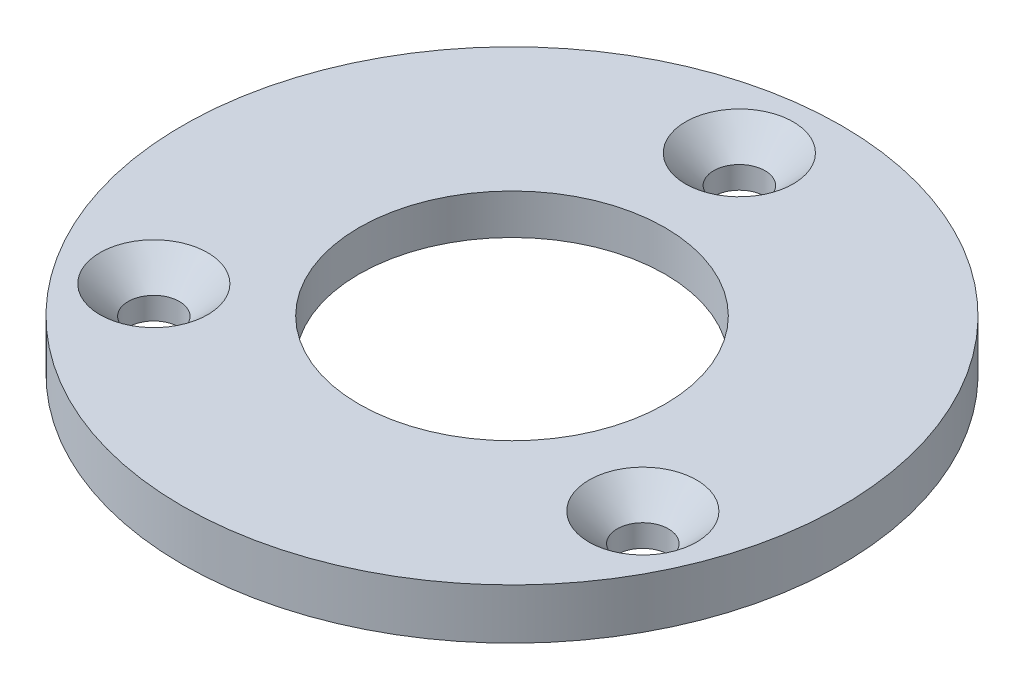
SolidWorks part; units mm, degrees
ref_plane "Front Plane" through (0, 0, 0) normal (0, 0, 1) x (1, 0, 0)
ref_plane "Top Plane" through (0, 0, 0) normal (0, 1, 0) x (1, 0, 0)
ref_plane "Right Plane" through (0, 0, 0) normal (1, 0, 0) x (0, 0, -1)
sketch "Sketch1" plane through (0, 0, 0) normal (0, 0, 1) x (1, 0, 0)
  line L0 (0, 0) -> (0, 10.3527) construction
  line L1 (-9.5504, 0) -> (-20.574, 0)
  line L2 (-20.574, 0) -> (-20.574, -3.1496)
  line L3 (-20.574, -3.1496) -> (-13.208, -3.1496)
  line L4 (-13.208, -3.1496) -> (-13.208, -2.5146)
  line L5 (-13.208, -2.5146) -> (-9.5504, -2.5146)
  line L6 (-9.5504, -2.5146) -> (-9.5504, 0)
  dimension "D1" = 20.574
  dimension "D2" = 9.5504
  dimension "D3" = 13.208
  dimension "D4" = 3.1496
  dimension "D5" = 0.635
revolve "Revolve1" add sketch "Sketch1" angle 360 about L0
hole_wizard "CSK for M3 SFHCS1" positions "Sketch3" profile "Sketch2" countersink size "M3" standard "ANSI Metric" end condition through all
sketch "Sketch3" plane through (0, 0, 0) normal (0, 1, 0) x (1, 0, 0)
  circle A0 centre (0, 0) radius 16.002 construction
  point P6 (-1.7156, 15.9098)
  point P15 (14.6361, -6.4691)
  point P16 (-12.9205, -9.4406)
  point P17 (0, 0)
  dimension "D1" = 32.004
  dimension "D2" = 3
sketch "Sketch2" plane through (0, 0, 0) normal (1, 0, 0) x (0, 0, 1)
  line L0 (0, 0) -> (0, 3.1496)
  line L1 (0, 3.1496) -> (1.6, 3.1496)
  line L2 (1.6, 3.1496) -> (1.6, 1.76)
  line L3 (1.6, 1.76) -> (3.36, 0)
  line L5 (3.36, 0) -> (0, 0)
  line L6 (-1.6, 1.76) -> (-3.36, 0) construction
  line L11 (0, -6.35) -> (0, 107.95) construction
  dimension "Thru Hole Dia." = 3.2
  dimension "Thru Hole Depth" = 3.1496
  dimension "Near C'Sink Dia." = 6.72
  dimension "Near C'Sink Angle" = 90
